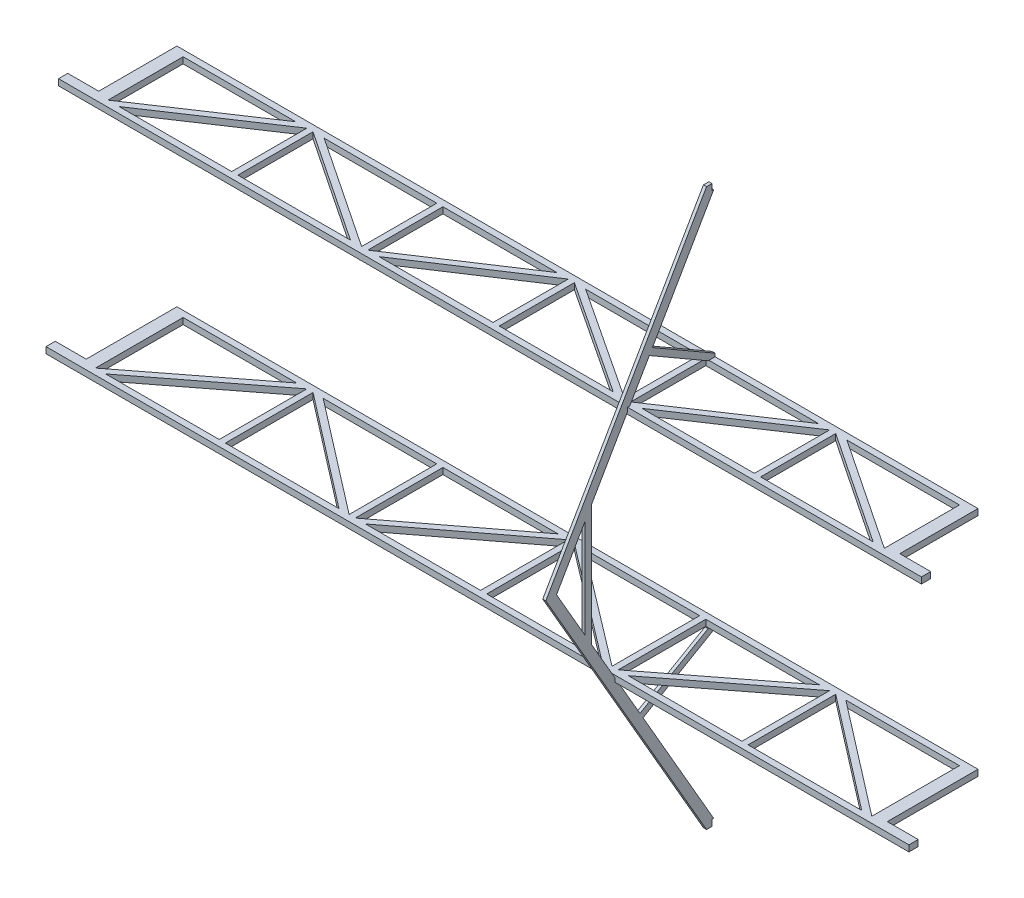
SolidWorks part; units mm, degrees
ref_plane "Спереди" through (0, 0, 0) normal (0, 0, 1) x (1, 0, 0)
ref_plane "Сверху" through (0, 0, 0) normal (0, 1, 0) x (1, 0, 0)
ref_plane "Справа" through (0, 0, 0) normal (1, 0, 0) x (0, 0, -1)
other "Configuration Table"
sketch "Эскиз2" plane through (-13650, 0, 0) normal (-1, 0, 0) x (0, 0, 1)
  line L0 (2771.2813, 4500) -> (-3463.5444, 4500) construction
  line L1 (2771.2813, 4500) -> (144.3376, 9050) construction
  line L2 (144.3376, 9050) -> (0, 9050) construction
  line L3 (-455.6624, 9050) -> (144.3376, 9050) construction
  line L4 (0, 9050) -> (0, 4500) construction
  line L5 (0, 8797) -> (0, 1803) construction
  line L6 (2598.0762, 4500) -> (0, 9000) construction
  line L7 (2598.0762, 4500) -> (0, 0) construction
  line L8 (0, 6550) -> (1414.5082, 6550)
  line L9 (0, 6550) -> (0, 6450)
  line L10 (0, 6450) -> (1414.5082, 6450)
  line L11 (1414.5082, 6550) -> (1414.5082, 6450)
  line L12 (0, 2800) -> (1616.5808, 2800)
  line L13 (0, 2800) -> (0, 2900)
  line L14 (0, 2900) -> (1616.5808, 2900)
  line L15 (1616.5808, 2800) -> (1616.5808, 2900)
  line L16 (-150, 2900) -> (-2900, 2900) construction
  line L17 (-150, 2800) -> (-2900, 2800) construction
  line L18 (-2900, 6600) -> (-150, 6600) construction
  dimension "D1" = 100
  dimension "D2" = 50
extrude "Бобышка-Вытянуть2" add sketch "Эскиз2" against normal blind 14150 separate body
sketch "Эскиз3" plane through (0, 2800, 0) normal (0, -1, 0) x (1, 0, 0)
  line L0 (-13550, 2005.0045) -> (-13550, 1466.5808)
  line L1 (-13550, 1466.5808) -> (-13050, 1466.5808)
  line L2 (-13050, 1466.5808) -> (-13050, -834.9582)
  line L3 (-13050, -834.9582) -> (-14812.7359, -834.9582)
  line L4 (-14812.7359, -834.9582) -> (-14812.7359, 2005.0045)
  line L5 (-14812.7359, 2005.0045) -> (-13550, 2005.0045)
  line L6 (-6575, 1616.5808) -> (-6575, -1235.4978) construction
  line L7 (500, 1616.5808) -> (-13650, 1616.5808) construction
  line L8 (1662.7359, -834.9582) -> (1662.7359, 2005.0045)
  line L9 (-100, -834.9582) -> (1662.7359, -834.9582)
  line L10 (-100, 1466.5808) -> (-100, -834.9582)
  line L11 (400, 1466.5808) -> (-100, 1466.5808)
  line L12 (400, 2005.0045) -> (400, 1466.5808)
  line L13 (1662.7359, 2005.0045) -> (400, 2005.0045)
  line L14 (-13650, 0) -> (-13650, 1616.5808) construction
  point P18 (-13550, 1735.7926)
  point P19 (-13300, 1466.5808)
  dimension "D1" = 600
  dimension "D2" = 100
  dimension "D3" = 150
extrude "Вырез-Вытянуть1" cut sketch "Эскиз3" against normal blind 1162
sketch "Эскиз4" plane through (0, 6450, 0) normal (0, -1, 0) x (1, 0, 0)
  line L0 (-13550, 2172.3908) -> (-13550, 1264.5082)
  line L1 (-13550, 1264.5082) -> (-13050, 1264.5082)
  line L2 (-13050, 1264.5082) -> (-13050, -667.5719)
  line L3 (-13050, -667.5719) -> (-15150.6166, -667.5719)
  line L4 (-15150.6166, -667.5719) -> (-15150.6166, 2172.3908)
  line L5 (-15150.6166, 2172.3908) -> (-13550, 2172.3908)
  line L6 (-6575, 1414.5082) -> (-6575, -1068.1116) construction
  line L8 (2000.6166, -667.5719) -> (2000.6166, 2172.3908)
  line L9 (-100, -667.5719) -> (2000.6166, -667.5719)
  line L10 (-100, 1264.5082) -> (-100, -667.5719)
  line L11 (400, 1264.5082) -> (-100, 1264.5082)
  line L12 (400, 2172.3908) -> (400, 1264.5082)
  line L13 (2000.6166, 2172.3908) -> (400, 2172.3908)
  line L15 (500, 1414.5082) -> (-13650, 1414.5082) construction
  line L16 (500, 1414.5082) -> (500, 0) construction
  dimension "D1" = 600
  dimension "D2" = 150
extrude "Вырез-Вытянуть2" cut sketch "Эскиз4" against normal blind 1162
sketch "Эскиз5" plane through (0, 2800, 0) normal (0, -1, 0) x (1, 0, 0)
  line L0 (-12850, 1516.5808) -> (-12850, 100)
  line L1 (-12850, 100) -> (-11013.7173, 100)
  line L2 (-11013.7173, 100) -> (-12850, 1516.5808)
  line L3 (-12686.2827, 1516.5808) -> (-10850, 100)
  line L4 (-12686.2827, 1516.5808) -> (-10850, 1516.5808)
  line L5 (-10850, 1516.5808) -> (-10850, 100)
  line L6 (400, 1616.5808) -> (-13550, 1616.5808) construction
  line L7 (-100, 0) -> (-13050, 0) construction
  line L8 (-13050, 0) -> (-13050, 1466.5808) construction
  line L9 (-10800, 2686.8519) -> (-10800, -871.2141) construction
  line L10 (-8750, 100) -> (-10586.2827, 100)
  line L11 (-8750, 1516.5808) -> (-8750, 100)
  line L12 (-10586.2827, 100) -> (-8750, 1516.5808)
  line L13 (-8913.7173, 1516.5808) -> (-10750, 1516.5808)
  line L14 (-8913.7173, 1516.5808) -> (-10750, 100)
  line L15 (-10750, 1516.5808) -> (-10750, 100)
  line L16 (-6575, 1616.5808) -> (-6575, -673.0634) construction
  line L17 (-8650, 1516.5808) -> (-8650, 100)
  line L18 (-8650, 100) -> (-6790.0437, 100)
  line L19 (-6790.0437, 100) -> (-8650, 1516.5808)
  line L20 (-8484.9563, 1516.5808) -> (-6625, 100)
  line L21 (-8484.9563, 1516.5808) -> (-6625, 1516.5808)
  line L22 (-6625, 1516.5808) -> (-6625, 100)
  line L23 (-4665.0437, 1516.5808) -> (-6525, 1516.5808)
  line L24 (-6525, 1516.5808) -> (-6525, 100)
  line L25 (-4665.0437, 1516.5808) -> (-6525, 100)
  line L26 (-6359.9563, 100) -> (-4500, 1516.5808)
  line L27 (-4500, 100) -> (-6359.9563, 100)
  line L28 (-4500, 1516.5808) -> (-4500, 100)
  line L29 (-4400, 1516.5808) -> (-4400, 100)
  line L30 (-2563.7173, 100) -> (-4400, 1516.5808)
  line L31 (-4400, 100) -> (-2563.7173, 100)
  line L32 (-4236.2827, 1516.5808) -> (-2400, 100)
  line L33 (-2400, 1516.5808) -> (-2400, 100)
  line L34 (-4236.2827, 1516.5808) -> (-2400, 1516.5808)
  line L35 (-463.7173, 1516.5808) -> (-2300, 1516.5808)
  line L36 (-463.7173, 1516.5808) -> (-2300, 100)
  line L37 (-2300, 1516.5808) -> (-2300, 100)
  line L38 (-300, 100) -> (-2136.2827, 100)
  line L39 (-300, 1516.5808) -> (-300, 100)
  line L40 (-2136.2827, 100) -> (-300, 1516.5808)
  dimension "D1" = 100
  dimension "D2" = 100
  dimension "D3" = 100
  dimension "D4" = 200
  dimension "D5" = 50
  dimension "D6" = 2000
  dimension "D7" = 100
  dimension "D8" = 50
  dimension "D9" = 100
extrude "Вырез-Вытянуть3" cut sketch "Эскиз5" against normal blind 1162
sketch "Эскиз6" plane through (0, 6450, 0) normal (0, -1, 0) x (1, 0, 0)
  line L0 (-12850, 1314.5082) -> (-12850, 100)
  line L1 (-12850, 100) -> (-11030.1468, 100)
  line L2 (-11030.1468, 100) -> (-12850, 1314.5082)
  line L3 (-12669.8532, 1314.5082) -> (-10850, 100)
  line L4 (-12669.8532, 1314.5082) -> (-10850, 1314.5082)
  line L5 (-10850, 1314.5082) -> (-10850, 100)
  line L9 (-10800, 2095.8137) -> (-10800, -1462.2522) construction
  line L10 (-8750, 100) -> (-10569.8532, 100)
  line L11 (-8750, 1314.5082) -> (-8750, 100)
  line L12 (-10569.8532, 100) -> (-8750, 1314.5082)
  line L13 (-8930.1468, 1314.5082) -> (-10750, 1314.5082)
  line L14 (-8930.1468, 1314.5082) -> (-10750, 100)
  line L15 (-10750, 1314.5082) -> (-10750, 100)
  line L16 (-6575, 743.3958) -> (-6575, 0) construction
  line L17 (-8650, 1314.5082) -> (-8650, 100)
  line L18 (-8650, 100) -> (-6806.7522, 100)
  line L19 (-6806.7522, 100) -> (-8650, 1314.5082)
  line L20 (-8468.2478, 1314.5082) -> (-6625, 100)
  line L21 (-8468.2478, 1314.5082) -> (-6625, 1314.5082)
  line L22 (-6625, 1314.5082) -> (-6625, 100)
  line L23 (-4681.7522, 1314.5082) -> (-6525, 1314.5082)
  line L24 (-6525, 1314.5082) -> (-6525, 100)
  line L25 (-4681.7522, 1314.5082) -> (-6525, 100)
  line L26 (-6343.2478, 100) -> (-4500, 1314.5082)
  line L27 (-4500, 100) -> (-6343.2478, 100)
  line L28 (-4500, 1314.5082) -> (-4500, 100)
  line L29 (-4400, 1314.5082) -> (-4400, 100)
  line L30 (-2580.1468, 100) -> (-4400, 1314.5082)
  line L31 (-4400, 100) -> (-2580.1468, 100)
  line L32 (-4219.8532, 1314.5082) -> (-2400, 100)
  line L33 (-2400, 1314.5082) -> (-2400, 100)
  line L34 (-4219.8532, 1314.5082) -> (-2400, 1314.5082)
  line L35 (-480.1468, 1314.5082) -> (-2300, 1314.5082)
  line L36 (-480.1468, 1314.5082) -> (-2300, 100)
  line L37 (-2300, 1314.5082) -> (-2300, 100)
  line L38 (-300, 100) -> (-2119.8532, 100)
  line L39 (-300, 1314.5082) -> (-300, 100)
  line L40 (-2119.8532, 100) -> (-300, 1314.5082)
  line L41 (-100, 0) -> (-13050, 0) construction
  line L42 (400, 1414.5082) -> (-13550, 1414.5082) construction
  line L43 (-13050, 0) -> (-13050, 1264.5082) construction
  dimension "D1" = 100
  dimension "D2" = 100
  dimension "D3" = 100
  dimension "D4" = 200
  dimension "D5" = 50
  dimension "D6" = 2000
  dimension "D7" = 100
  dimension "D8" = 50
  dimension "D9" = 100
extrude "Вырез-Вытянуть4" cut sketch "Эскиз6" against normal blind 1162
sketch "Эскиз7" plane through (-4400, 0, 0) normal (1, 0, 0) x (0, 0, -1)
  line L0 (-2736.6403, 4500) -> (-138.5641, 9000)
  line L2 (-2771.2813, 4500) -> (3463.5444, 4500) construction
  line L3 (-138.5641, 9000) -> (-50, 9000)
  line L5 (-50, 9000) -> (-50, 8900)
  line L11 (0, 9050) -> (0, 4500) construction
  line L12 (0, 9000) -> (-50, 9000) construction
  line L13 (0, 9000) -> (0, 8900) construction
  line L14 (0, 8900) -> (-50, 8900) construction
  line L15 (-50, 9000) -> (-50, 8900) construction
  line L16 (0, 9050) -> (-100, 9050) construction
  line L17 (0, 9050) -> (0, 9000) construction
  line L18 (0, 9000) -> (-100, 9000) construction
  line L19 (-100, 9050) -> (-100, 9000) construction
  line L20 (-23.094, 8900) -> (-1013.2497, 7185)
  line L21 (-2771.2813, 4500) -> (-144.3376, 9050) construction
  line L22 (-50, 8900) -> (-23.094, 8900)
  line L23 (-2100, 5302.6933) -> (-2100, 3697.3067)
  line L24 (-2000, 5475.8984) -> (-2000, 3524.1016)
  line L25 (-2100, 5302.6933) -> (-2563.4352, 4500)
  line L26 (0, 6450) -> (-1414.5082, 6450) construction
  line L27 (0, 2900) -> (-1466.5808, 2900) construction
  line L28 (-2736.6403, 4500) -> (0, 4500) construction
  line L29 (-2100, 3697.3067) -> (-2563.4352, 4500)
  line L30 (-23.094, 100) -> (-1164.8042, 2077.5)
  line L31 (-50, 100) -> (-23.094, 100)
  line L32 (-50, 0) -> (-50, 100)
  line L33 (-138.5641, 0) -> (-50, 0)
  line L34 (-2736.6403, 4500) -> (-138.5641, 0)
  line L35 (-1063.2497, 7098.3975) -> (-113.3975, 6550)
  line L36 (0, 6550) -> (-1414.5082, 6550) construction
  line L37 (-113.3975, 6550) -> (0, 6550)
  line L38 (0, 6550) -> (0, 6600)
  line L39 (0, 6600) -> (-1013.2497, 7185)
  line L40 (-1063.2497, 7098.3975) -> (-2000, 5475.8984)
  line L41 (-1214.8042, 2164.1025) -> (-113.3975, 2800)
  line L42 (0, 2800) -> (-1616.5808, 2800) construction
  line L43 (-113.3975, 2800) -> (0, 2800)
  line L44 (0, 2800) -> (0, 2750)
  line L45 (0, 2750) -> (-1164.8042, 2077.5)
  line L46 (-1214.8042, 2164.1025) -> (-2000, 3524.1016)
  point P33 (-2100, 4500)
  point P34 (-2000, 4500)
  dimension "D1" = 50
  dimension "D2" = 100
  dimension "D3" = 100
  dimension "D4" = 30
  dimension "D5" = 150
  dimension "D6" = 100
  dimension "D7" = 2000
  dimension "D8" = 3550
  dimension "D9" = 100
  dimension "D10" = 50
  dimension "D11" = 100
  dimension "D12" = 50
extrude "Бобышка-Вытянуть3" add sketch "Эскиз7" along normal blind 50 separate body
